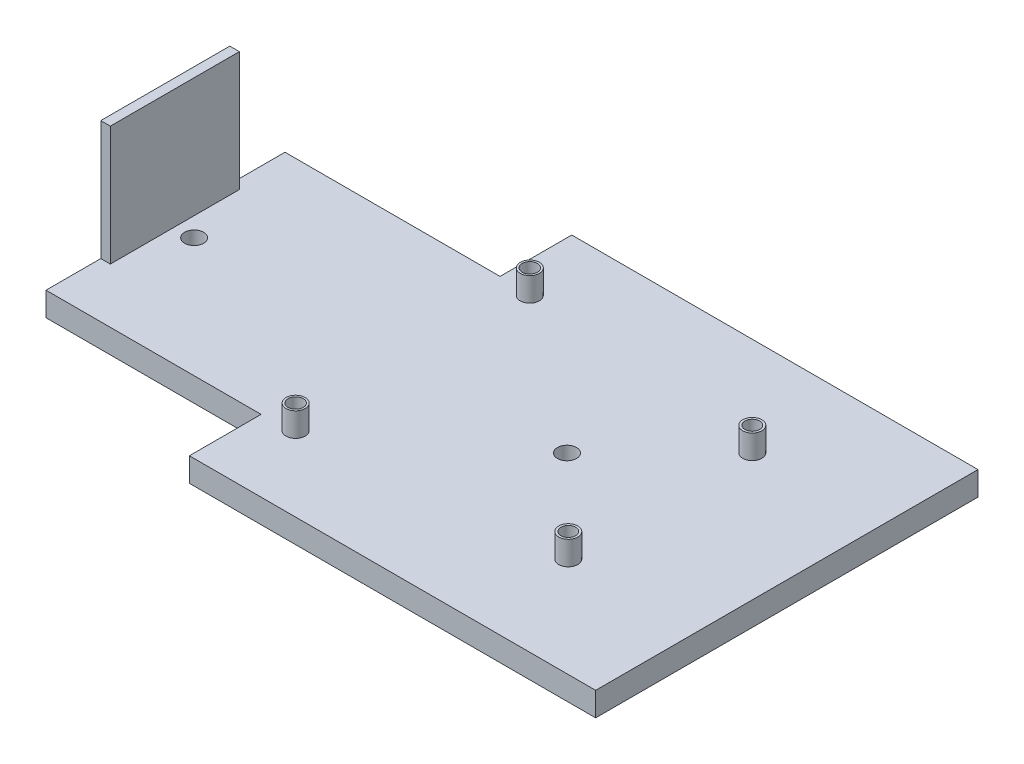
SolidWorks part; units mm, degrees
ref_plane "Front Plane" through (0, 0, 0) normal (0, 0, 1) x (1, 0, 0)
ref_plane "Top Plane" through (0, 0, 0) normal (0, 1, 0) x (1, 0, 0)
ref_plane "Right Plane" through (0, 0, 0) normal (1, 0, 0) x (0, 0, -1)
sketch "Sketch2" plane through (0, 0, 0) normal (0, 1, 0) x (1, 0, 0)
  line L0 (-113.563, 63.9567) -> (-113.563, 78.9567)
  line L1 (-158.563, 63.9567) -> (-113.563, 63.9567)
  line L2 (-158.563, 63.9567) -> (-158.563, 13.9567)
  line L3 (-158.563, 13.9567) -> (-113.563, 13.9567)
  line L7 (-113.563, 78.9567) -> (-28.563, 78.9567)
  line L8 (-28.563, 78.9567) -> (-28.563, -1.0433)
  line L9 (-28.563, -1.0433) -> (-113.563, -1.0433)
  line L10 (-113.563, -1.0433) -> (-113.563, 13.9567)
  point P0 (-113.563, 38.9567)
  dimension "D1" = 45
  dimension "D3" = 15
  dimension "D4" = 85
  dimension "D5" = 15
  dimension "D6" = 85
extrude "Boss-Extrude2" add sketch "Sketch2" along normal blind 5
sketch "Sketch3" plane through (0, 5, 0) normal (0, 1, 0) x (1, 0, 0)
  circle A0 centre (-74.563, 38.9567) radius 2
  circle A1 centre (-152.563, 38.9567) radius 2
extrude "Cut-Extrude1" cut sketch "Sketch3" against normal blind 18
sketch "Sketch6" plane through (0, 5, 0) normal (0, 1, 0) x (1, 0, 0)
  circle A0 centre (-107.0067, 63.6239) radius 2
  circle A1 centre (-107.0067, 63.6239) radius 1.5961
  circle A2 centre (-107.0067, 14.6239) radius 2
  circle A3 centre (-107.0067, 14.6239) radius 1.5962
  circle A4 centre (-55.2067, 19.8739) radius 1.5463
  circle A5 centre (-55.2067, 19.8739) radius 2
  circle A6 centre (-55.2067, 58.3739) radius 2
  circle A7 centre (-55.2067, 58.3739) radius 1.5463
extrude "Boss-Extrude3" add sketch "Sketch6" along normal blind 5
sketch "Sketch9" plane through (0, 5, 0) normal (0, 1, 0) x (1, 0, 0)
  line L0 (-158.563, 52.4127) -> (-156.563, 52.4127)
  line L1 (-158.563, 63.9567) -> (-158.563, 13.9567) construction
  line L2 (-156.563, 52.4127) -> (-156.563, 25.4127)
  line L3 (-156.563, 25.4127) -> (-158.563, 25.4127)
  line L4 (-158.563, 25.4127) -> (-158.563, 52.4127)
  dimension "D1" = 2
extrude "Boss-Extrude5" add sketch "Sketch9" along normal blind 25
